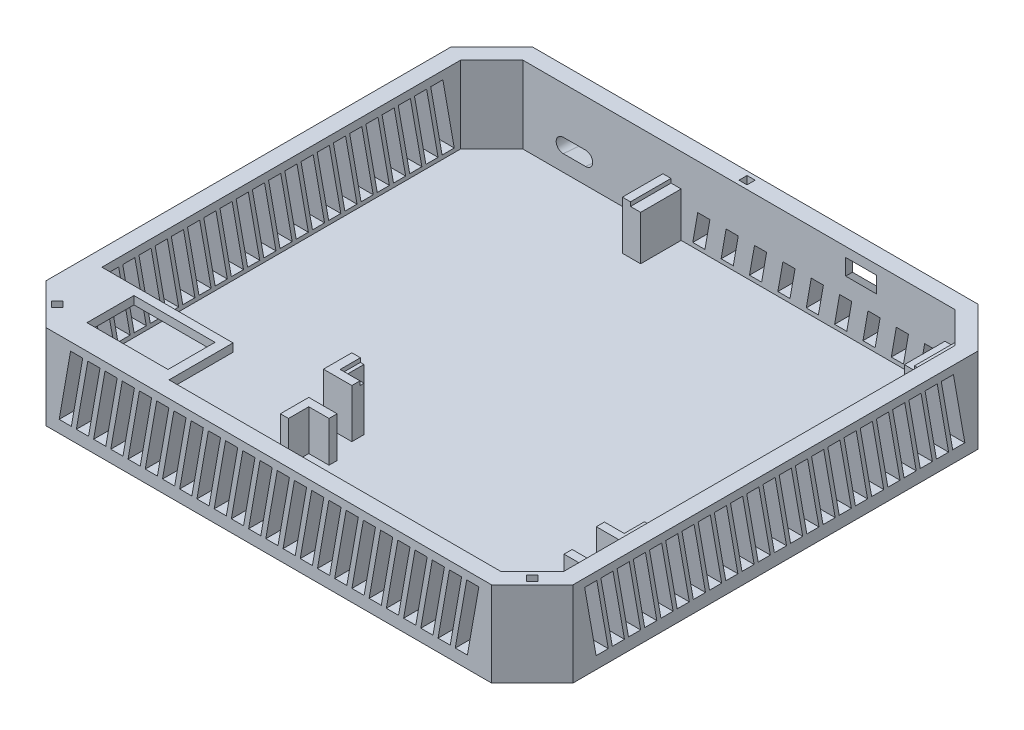
SolidWorks part; units mm, degrees
ref_plane "Front Plane" through (0, 0, 0) normal (0, 0, 1) x (1, 0, 0)
ref_plane "Top Plane" through (0, 0, 0) normal (0, 1, 0) x (1, 0, 0)
ref_plane "Right Plane" through (0, 0, 0) normal (1, 0, 0) x (0, 0, -1)
sketch "Sketch2" plane through (0, 0, 0) normal (0, 1, 0) x (1, 0, 0)
  line L0 (-55, 60) -> (-65, 50)
  line L1 (-55, 60) -> (55, 60)
  line L2 (-65, 50) -> (-65, -50)
  line L3 (-55, -60) -> (55, -60)
  line L4 (65, 50) -> (65, -50)
  line L5 (-65, -50) -> (-55, -60)
  line L6 (55, -60) -> (65, -50)
  line L7 (55, 60) -> (65, 50)
  point P0 (0, 0)
  point P1 (65, -60)
  point P2 (-65, 60)
  point P3 (-65, -60)
  point P4 (65, 60)
  point P14 (0, 60)
  point P15 (65, 0)
  dimension "D1" = 120
  dimension "D2" = 110
extrude "Boss-Extrude1" add sketch "Sketch2" against normal blind 21
shell "Shell3" thickness 4
sketch "Sketch3" plane through (0, 0, 0) normal (0, 1, 0) x (1, 0, 0)
  line L0 (55, 60) -> (-55, 60) construction
  line L1 (-1, 59) -> (1, 59)
  line L2 (-1, 59) -> (-1, 57)
  line L3 (-1, 57) -> (1, 57)
  line L4 (1, 59) -> (1, 57)
  line L5 (-1, 59) -> (1, 57) construction
  line L6 (-1, 57) -> (1, 59) construction
  line L7 (53.3431, 56) -> (-53.3431, 56) construction
  line L8 (53.3431, -56) -> (61, -48.3431) construction
  line L9 (57.1716, -53.5858) -> (58.5858, -52.1716)
  line L10 (57.1716, -53.5858) -> (58.5858, -55)
  line L11 (58.5858, -55) -> (60, -53.5858)
  line L12 (58.5858, -52.1716) -> (60, -53.5858)
  line L13 (57.1716, -53.5858) -> (60, -53.5858) construction
  line L14 (58.5858, -55) -> (58.5858, -52.1716) construction
  line L15 (57.1716, -52.1716) -> (60, -55) construction
  line L16 (55, -60) -> (65, -50) construction
  line L17 (0, 60) -> (0, -60) construction
  line L18 (-55, -60) -> (55, -60) construction
  line L19 (-58.5858, -52.1716) -> (-60, -53.5858)
  line L20 (-58.5858, -55) -> (-60, -53.5858)
  line L21 (-57.1716, -53.5858) -> (-58.5858, -52.1716)
  line L22 (-57.1716, -53.5858) -> (-58.5858, -55)
  point P0 (0, 58)
  point P7 (0, 60)
  point P8 (0, 59)
  point P11 (58.5858, -53.5858)
  point P18 (57.8787, -52.8787)
  dimension "D1" = 2
  dimension "D2" = 1
  dimension "D3" = 2
  dimension "D4" = 1
  dimension "D5" = 1
extrude "Cut-Extrude1" cut sketch "Sketch3" against normal blind 2
sketch "Sketch5" plane through (-61, 0, 0) normal (-1, 0, 0) x (0, 0, 1)
  line L0 (-43.9325, -2) -> (-40.9325, -2)
  line L1 (-40.9325, -2) -> (-43.7538, -18)
  line L2 (-43.7538, -18) -> (-46.7538, -18)
  line L3 (-46.7538, -18) -> (-43.9325, -2)
  line L5 (-50, 0) -> (50, 0) construction
  line L7 (-48.3431, -19) -> (-48.3431, 0) construction
  line L8 (-48.3431, -19) -> (48.3431, -19) construction
  point P2 (-45.3431, -10)
  point P11 (-48.3431, -9.5)
extrude "Cut-Extrude3" cut sketch "Sketch5" against normal through all and the other way up to next
pattern_linear "LPattern2" count 23 spacing 4 along (0, 0, 1) of "Cut-Extrude3"
sketch "Sketch4" plane through (0, 0, 56) normal (0, 0, 1) x (1, 0, 0)
  line L0 (-48.9325, -2) -> (-45.9325, -2)
  line L1 (-45.9325, -2) -> (-48.7538, -18)
  line L2 (-48.7538, -18) -> (-51.7538, -18)
  line L3 (-51.7538, -18) -> (-48.9325, -2)
  line L4 (-55, 0) -> (55, 0) construction
  line L7 (-53.3431, -19) -> (53.3431, -19) construction
  line L8 (-53.3431, -19) -> (-53.3431, 0) construction
  point P8 (-50.3431, -10)
  point P11 (-53.3431, -9.5)
  dimension "D1" = 3
  dimension "D2" = 2
  dimension "D3" = 1
  dimension "D4" = 3
  dimension "D5" = 80
extrude "Cut-Extrude2" cut sketch "Sketch4" along normal up to next
pattern_linear "LPattern1" count 24 spacing 4.25 along (1, 0, 0) of "Cut-Extrude2"
sketch "Sketch7" plane through (0, -19, 0) normal (0, 1, 0) x (1, 0, 0)
  line L0 (53.3431, 56) -> (-53.3431, 56) construction
  line L1 (53.3431, 56) -> (-16.7569, 56) construction
  line L2 (53.3431, 56) -> (53.3431, -26.5) construction
  line L3 (53.3431, -26.5) -> (-16.7569, -26.5) construction
  line L4 (-16.7569, 56) -> (-16.7569, -26.5) construction
  line L5 (-18.7569, 56) -> (-18.7569, 46)
  line L6 (-16.878, -20.6506) -> (-15.878, -20.6506)
  line L7 (28.7735, 56) -> (34.3431, 56) construction
  line L8 (28.7735, 56) -> (28.7735, 52.8671) construction
  line L9 (28.7735, 52.8671) -> (34.3431, 52.8671) construction
  line L10 (34.3431, 56) -> (34.3431, 52.8671) construction
  line L11 (28.7735, 56) -> (34.3431, 52.8671) construction
  line L12 (28.7735, 52.8671) -> (34.3431, 56) construction
  line L13 (-18.7569, 46) -> (-14.2569, 46)
  line L16 (-15.878, -20.6506) -> (-15.878, -24.6506)
  line L17 (-15.878, -24.6506) -> (-11.878, -24.6506)
  line L18 (-18.7569, 56) -> (-14.2569, 56)
  line L19 (-14.2569, 56) -> (-14.2569, 46)
  line L20 (-11.878, -24.6506) -> (-11.878, -25.6506)
  line L21 (18.2931, -26.5) -> (18.2931, 56) construction
  line L22 (-18.878, -20.6506) -> (-18.878, -27.6506)
  line L23 (-18.878, -27.6506) -> (-11.878, -27.6506)
  line L24 (-11.878, -27.6506) -> (-11.878, -25.6506)
  line L27 (-16.878, -20.6506) -> (-18.878, -20.6506)
  point P8 (31.5583, 54.4335)
  dimension "D1" = 82.5
  dimension "D2" = 70.1
  dimension "D3" = 3.1329
  dimension "D4" = 5.5696
  dimension "D5" = 19
  dimension "D6" = 2
  dimension "D7" = 2.5
  dimension "D8" = 10
  dimension "D9" = 2
  dimension "D10" = 2
  dimension "D11" = 7
  dimension "D12" = 7
  dimension "D13" = 1
  dimension "D14" = 1
  dimension "D15" = 5.8494
extrude "Boss-Extrude2" add sketch "Sketch7" along normal blind 12
sketch "Sketch8" plane through (0, -7, 0) normal (0, 1, 0) x (1, 0, 0)
  line L0 (-16.7569, 56) -> (-16.7569, 46)
  line L3 (-16.7569, 46) -> (-14.2569, 46)
  line L4 (-14.2569, 46) -> (-14.2569, 56)
  line L5 (-14.2569, 56) -> (-16.7569, 56)
  line L6 (-16.7569, 56) -> (-16.7569, -26.5) construction
  line L8 (-14.2569, 56) -> (-14.2569, 46) construction
  line L9 (-18.7569, 46) -> (-14.2569, 46) construction
  line L10 (-18.7569, 56) -> (-14.2569, 56) construction
  line L25 (-16.7569, -20.6506) -> (-15.878, -20.6506)
  line L26 (-15.878, -20.6506) -> (-15.878, -24.6506)
  line L27 (-15.878, -24.6506) -> (-11.878, -24.6506)
  line L28 (-11.878, -24.6506) -> (-11.878, -25.6506)
  line L29 (-11.878, -25.6506) -> (-16.7569, -25.6506)
  line L30 (-16.7569, -25.6506) -> (-16.7569, -20.6506)
extrude "Cut-Extrude6" cut sketch "Sketch8" against normal blind 1
ref_plane "Plane3" through (18.2931, 0, 0) normal (-1, 0, 0) x (0, 0, 1)
mirror "Mirror3" about plane through (18.2931, 0, 0) normal (-1, 0, 0) of "Cut-Extrude6", "Boss-Extrude2"
sketch "Sketch9" plane through (0, 0, -56) normal (0, 0, 1) x (1, 0, 0)
  line L0 (53.3431, -7) -> (53.3431, 0) construction
  line L1 (26.3431, -2.34) -> (33.9431, -2.34)
  line L2 (26.3431, -2.34) -> (26.3431, -6.34)
  line L3 (26.3431, -6.34) -> (33.9431, -6.34)
  line L4 (33.9431, -2.34) -> (33.9431, -6.34)
  line L5 (26.3431, -2.34) -> (33.9431, -6.34) construction
  line L6 (26.3431, -6.34) -> (33.9431, -2.34) construction
  line L8 (53.3431, -8) -> (50.8431, -8) construction
  point P0 (30.1431, -4.34)
  dimension "D1" = 4
  dimension "D2" = 7.6
  dimension "D3" = 19.4
  dimension "D4" = 1.66
extrude "Cut-Extrude7" cut sketch "Sketch9" against normal up to next (4 mm away) draft 30
sketch "Sketch10" plane through (0, -19, 0) normal (0, 1, 0) x (1, 0, 0)
  line L0 (53.3431, -35.5) -> (53.3431, -33.5)
  line L1 (53.3431, -35.5) -> (53.3431, -54) construction
  line L2 (53.3431, -35.5) -> (-14.6569, -35.5) construction
  line L3 (-14.6569, -35.5) -> (-14.6569, -54) construction
  line L4 (53.3431, -54) -> (-14.6569, -54) construction
  line L5 (53.3431, -33.5) -> (48.3431, -33.5)
  line L6 (48.3431, -33.5) -> (48.3431, -35.5)
  line L7 (48.3431, -35.5) -> (53.3431, -35.5)
  line L8 (53.3431, -44.75) -> (-14.6569, -44.75) construction
  line L9 (19.3431, -35.5) -> (19.3431, -54) construction
  line L10 (48.3431, -56) -> (48.3431, -54)
  line L11 (48.3431, -54) -> (53.3431, -54)
  line L12 (53.3431, -56) -> (48.3431, -56)
  line L13 (53.3431, -54) -> (53.3431, -56)
  line L14 (-9.6569, -56) -> (-9.6569, -54)
  line L18 (-9.6569, -54) -> (-14.6569, -54)
  line L19 (-9.6569, -35.5) -> (-14.6569, -35.5)
  line L20 (-16.6569, -33.5) -> (-9.6569, -33.5)
  line L21 (-9.6569, -33.5) -> (-9.6569, -35.5)
  line L22 (-53.3431, -56) -> (53.3431, -56) construction
  line L24 (-16.6569, -33.5) -> (-16.6569, -40.5)
  line L25 (-14.6569, -35.5) -> (-14.6569, -40.5)
  line L26 (-14.6569, -40.5) -> (-16.6569, -40.5)
  line L27 (-16.6569, -56) -> (-16.6569, -49)
  line L28 (-9.6569, -56) -> (-16.6569, -56)
  line L29 (-14.6569, -49) -> (-16.6569, -49)
  line L30 (-14.6569, -54) -> (-14.6569, -49)
  dimension "D3" = 2
  dimension "D1" = 68
  dimension "D2" = 18.5
  dimension "D4" = 2
  dimension "D5" = 7
  dimension "D6" = 2
  dimension "D7" = 5
  dimension "D8" = 7
extrude "Boss-Extrude3" add sketch "Sketch10" along normal blind 10
sketch "Sketch12" plane through (0, 0, 0) normal (0, 1, 0) x (1, 0, 0)
  line L0 (-53.3431, -56) -> (-28.6431, -56)
  line L1 (-53.3431, -56) -> (-16.6569, -56) construction
  line L2 (-28.6431, -56) -> (-28.6431, -40.2)
  line L3 (-28.6431, -40.2) -> (-61, -40.2)
  line L4 (-61, 48.3431) -> (-61, -48.3431) construction
  line L5 (-61, -40.2) -> (-61, -48.3431)
  line L6 (-61, -48.3431) -> (-53.3431, -56)
  line L8 (-50.9931, -42.3) -> (-30.9931, -42.3)
  line L9 (-50.9931, -42.3) -> (-50.9931, -53.9)
  line L10 (-50.9931, -53.9) -> (-30.9931, -53.9)
  line L11 (-30.9931, -42.3) -> (-30.9931, -53.9)
  line L12 (-50.9931, -42.3) -> (-30.9931, -53.9) construction
  line L13 (-50.9931, -53.9) -> (-30.9931, -42.3) construction
  point P9 (-40.9931, -48.1)
  point P16 (-30.9931, -48.1)
  point P17 (-28.6431, -48.1)
  point P18 (-40.9931, -53.9)
  point P19 (-40.9931, -56)
  dimension "D1" = 24.7
  dimension "D2" = 15.8
  dimension "D3" = 11.6
  dimension "D4" = 20
extrude "Boss-Extrude4" add sketch "Sketch12" against normal up to vertex
sketch "Sketch13" plane through (0, 0, -56) normal (0, 0, 1) x (1, 0, 0)
  line L0 (-43.3431, -13.25) -> (-37.8431, -13.25) construction
  line L1 (-43.3431, -11.5) -> (-37.8431, -11.5)
  line L2 (-43.3431, -15) -> (-37.8431, -15)
  line L3 (-18.7569, -19) -> (-53.3431, -19) construction
  line L4 (-53.3431, -19) -> (-53.3431, 0) construction
  arc A0 (-43.3431, -11.5) -> (-43.3431, -15) centre (-43.3431, -13.25) ccw
  arc A1 (-37.8431, -15) -> (-37.8431, -11.5) centre (-37.8431, -13.25) ccw
  point P2 (-40.5931, -13.25)
  point P7 (-45.0931, -13.25)
  point P8 (-36.0931, -13.25)
  dimension "D4" = 10
  dimension "D1" = 9
  dimension "D2" = 3.5
  dimension "D3" = 4
extrude "Cut-Extrude9" cut sketch "Sketch13" against normal up to next (4 mm away) draft 5 draft outward yes
sketch "Sketch14" plane through (0, 0, -56) normal (0, 0, -1) x (-1, 0, 0)
  line L0 (-48.8431, -11) -> (-47.6089, -18)
  line L1 (-47.6089, -18) -> (-44.6089, -18)
  line L2 (-44.6089, -18) -> (-45.8431, -11)
  line L3 (-45.8431, -11) -> (-48.8431, -11)
  line L7 (-50.8431, -19) -> (14.2569, -19) construction
  line L8 (-50.8431, -8) -> (-50.8431, -19) construction
  dimension "D1" = 80
  dimension "D2" = 7
  dimension "D3" = 3
  dimension "D4" = 2
  dimension "D5" = 1
extrude "Cut-Extrude10" cut sketch "Sketch14" along normal up to next
pattern_linear "LPattern3" count 9 spacing 7 along (-1, 0, 0) of "Cut-Extrude10"
sketch "Sketch15" plane through (0, -19, 0) normal (0, 1, 0) x (1, 0, 0)
  line L0 (-9.2569, 52) -> (-9.2569, 49)
  line L1 (-9.2569, 49) -> (45.8431, 39.2844)
  line L2 (45.8431, 39.2844) -> (45.8431, 42.2844)
  line L3 (45.8431, 42.2844) -> (-9.2569, 52)
  line L4 (-9.4528, -38.5) -> (-6.4528, -38.5)
  line L5 (-6.4528, -38.5) -> (-8.6569, -51)
  line L6 (-8.6569, -51) -> (-11.6569, -51)
  line L7 (-11.6569, -51) -> (-9.4528, -38.5)
  line L8 (-52.8146, 45.373) -> (-52.8146, 42.373)
  line L9 (-52.8146, 42.373) -> (-32.8146, 38.8464)
  line L10 (-32.8146, 38.8464) -> (-32.8146, 41.8464)
  line L11 (-32.8146, 41.8464) -> (-52.8146, 45.373)
  line L12 (-14.6569, -54) -> (-14.6569, -49) construction
  line L13 (-9.2569, 52) -> (45.8431, 52) construction
  line L14 (-9.2569, 52) -> (-9.2569, -23.6506) construction
  line L15 (-9.2569, -23.6506) -> (45.8431, -23.6506) construction
  line L16 (45.8431, 52) -> (45.8431, -23.6506) construction
  line L17 (-11.6569, -38.5) -> (50.3431, -38.5) construction
  line L18 (-11.6569, -38.5) -> (-11.6569, -51) construction
  line L19 (-11.6569, -51) -> (50.3431, -51) construction
  line L20 (50.8431, 56) -> (-14.2569, 56) construction
  line L21 (-18.878, -27.6506) -> (-11.878, -27.6506) construction
  line L22 (50.8431, 56) -> (50.8431, 46) construction
  line L23 (50.3431, -38.5) -> (50.3431, -51) construction
  line L24 (-9.6569, -54) -> (-14.6569, -54) construction
  line L25 (-14.6569, -35.5) -> (-9.6569, -35.5) construction
  line L26 (53.3431, -35.5) -> (53.3431, -33.5) construction
  point P10 (18.2931, 56)
  point P18 (18.2931, 52)
  dimension "D1" = 3
  dimension "D2" = 20
  dimension "D3" = 80
  dimension "D4" = 80
  dimension "D5" = 4
  dimension "D6" = 5
  dimension "D7" = 3
  dimension "D8" = 4
  dimension "D9" = 3
  dimension "D10" = 3
  dimension "D11" = 3
extrude "Cut-Extrude11" [suppressed] cut sketch "Sketch15" against normal up to next
